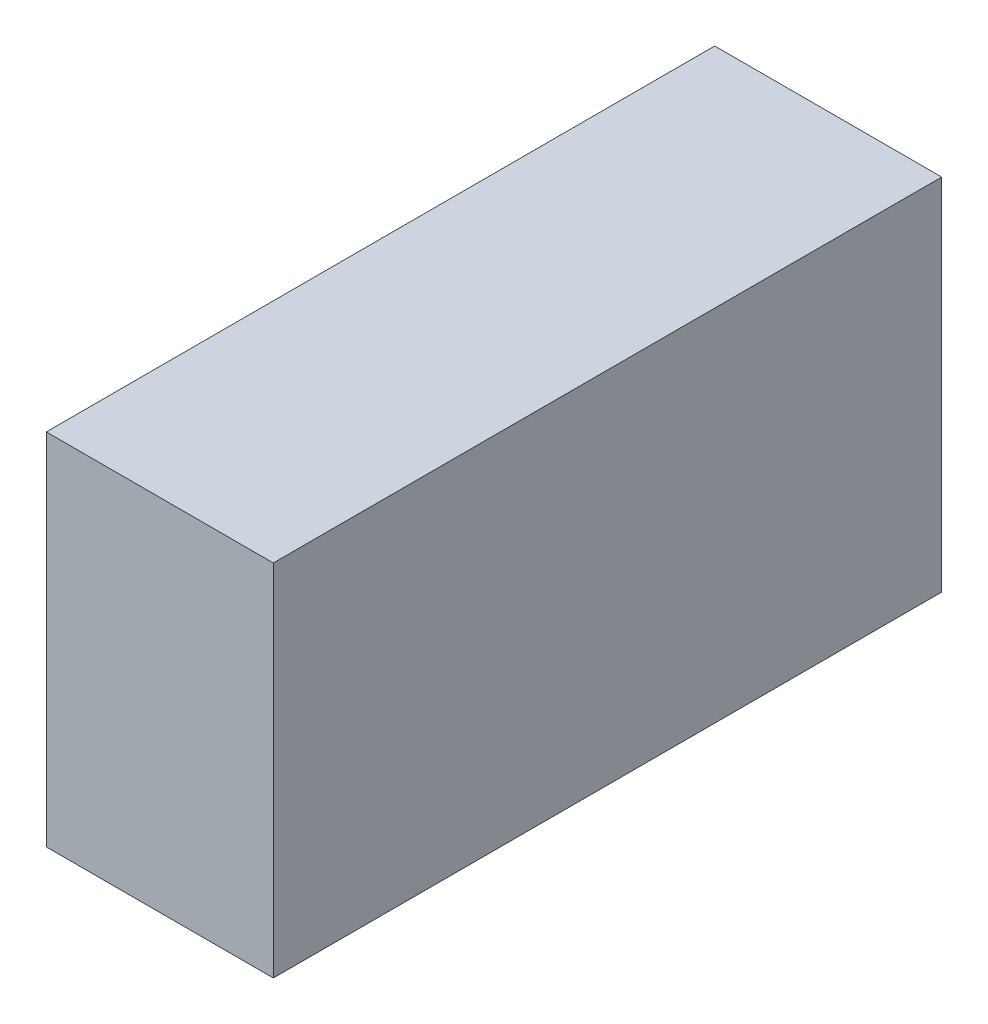
SolidWorks part; units mm, degrees
ref_plane "Front Plane" through (0, 0, 0) normal (0, 0, 1) x (1, 0, 0)
ref_plane "Top Plane" through (0, 0, 0) normal (0, 1, 0) x (1, 0, 0)
ref_plane "Right Plane" through (0, 0, 0) normal (1, 0, 0) x (0, 0, -1)
sketch "草圖1" plane through (0, 0, 0) normal (0, 0, 1) x (1, 0, 0)
  line L0 (-18, -28.5) -> (18, -28.5)
  line L1 (18, -28.5) -> (18, 28.5)
  line L2 (18, 28.5) -> (-18, 28.5)
  line L3 (-18, 28.5) -> (-18, -28.5)
extrude "填料-伸長1" add sketch "草圖1" along normal blind 106
